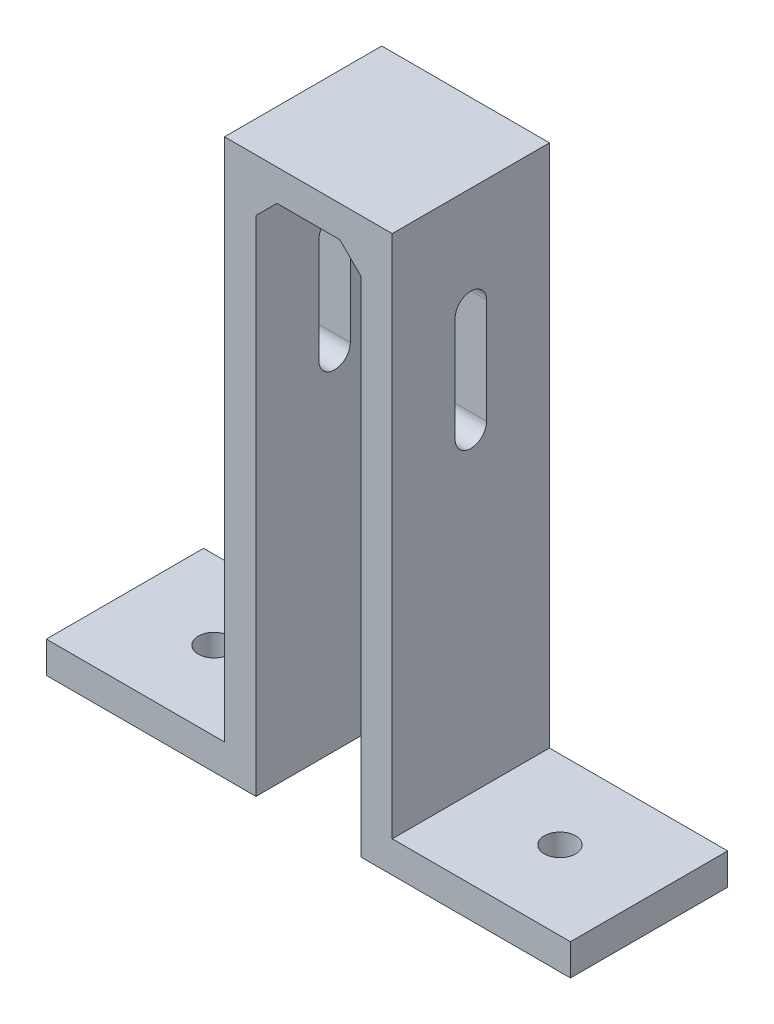
SolidWorks part; units mm, degrees
ref_plane "前视基准面" through (0, 0, 0) normal (0, 0, 1) x (1, 0, 0)
ref_plane "上视基准面" through (0, 0, 0) normal (0, 1, 0) x (1, 0, 0)
ref_plane "右视基准面" through (0, 0, 0) normal (1, 0, 0) x (0, 0, -1)
sketch "草图1" plane through (0, 0, 0) normal (0, 0, 1) x (1, 0, 0)
  line L0 (0, 0) -> (0, 50)
  line L1 (0, 50) -> (10, 50)
  line L2 (10, 50) -> (10, 0)
  line L3 (10, 0) -> (30, 0)
  line L4 (0, 0) -> (-20, 0)
  line L5 (13, 3) -> (30, 3)
  line L6 (13, 53) -> (13, 3)
  line L7 (-3, 53) -> (13, 53)
  line L8 (-3, 3) -> (-3, 53)
  line L9 (-3, 3) -> (-20, 3)
  line L10 (-20, 3) -> (-20, 0)
  line L11 (30, 3) -> (30, 0)
  dimension "D1" = 20
  dimension "D2" = 20
  dimension "D3" = 50
  dimension "D4" = 10
  dimension "D6" = 3
  dimension "D5" = 3
  dimension "D7" = 3
  dimension "D8" = 3
  dimension "D9" = 3
extrude "凸台-拉伸1" add sketch "草图1" along normal blind 15
sketch "草图2" plane through (13, 0, 0) normal (1, 0, 0) x (0, 0, -1)
  line L0 (-15, 53) -> (0, 53) construction
  line L1 (-15, 3) -> (-15, 53) construction
  circle A0 centre (-7.5, 43) radius 1.5
  dimension "D1" = 3
  dimension "D2" = 10
  dimension "D3" = 7.5
extrude "切除-拉伸1" cut sketch "草图2" against normal through all
sketch "草图4" plane through (13, 0, 0) normal (1, 0, 0) x (0, 0, -1)
  line L0 (-9, 43) -> (-9, 33)
  line L1 (-9, 33) -> (-6, 33)
  line L2 (-6, 33) -> (-6, 43)
  line L3 (-9, 43) -> (-6, 43)
  circle A0 centre (-7.5, 43) radius 1.5 construction
  circle A1 centre (-7.5, 33) radius 1.5
  circle M3 centre (-7.5, 43) radius 1.5
  dimension "D1" = 10
  dimension "D2" = 10
extrude "切除-拉伸2" cut sketch "草图4" against normal through all contours A1 L2 L0 M3 | L1 A1 | L1 A1
sketch "草图5" plane through (0, 3, 0) normal (0, 1, 0) x (1, 0, 0)
  line L0 (-20, -15) -> (-20, 0) construction
  line L1 (30, -15) -> (30, 0) construction
  line L3 (-3, -15) -> (-20, -15) construction
  line L4 (30, -15) -> (13, -15) construction
  circle A0 centre (-11.5, -7.5) radius 1.5
  circle A1 centre (21.5, -7.5) radius 1.5
  dimension "D1" = 3
  dimension "D2" = 3
  dimension "D3" = 8.5
  dimension "D4" = 8.5
  dimension "D5" = 7.5
  dimension "D6" = 7.5
extrude "切除-拉伸3" cut sketch "草图5" against normal through all
sketch "草图6" plane through (0, 0, 15) normal (0, 0, 1) x (1, 0, 0)
  line L0 (0, 50) -> (2, 50)
  line L1 (0, 50) -> (10, 50) construction
  line L2 (2, 50) -> (0, 48)
  line L3 (0, 0) -> (0, 50) construction
  line L4 (0, 48) -> (0, 50)
  line L5 (10, 50) -> (8, 50)
  line L6 (8, 50) -> (10, 48)
  line L7 (10, 50) -> (10, 0) construction
  line L8 (10, 48) -> (10, 50)
  dimension "D1" = 2
  dimension "D2" = 2
  dimension "D3" = 2
extrude "凸台-拉伸2" add sketch "草图6" against normal up to surface (15 mm away) up to face at (5, 18.1667, 0)
